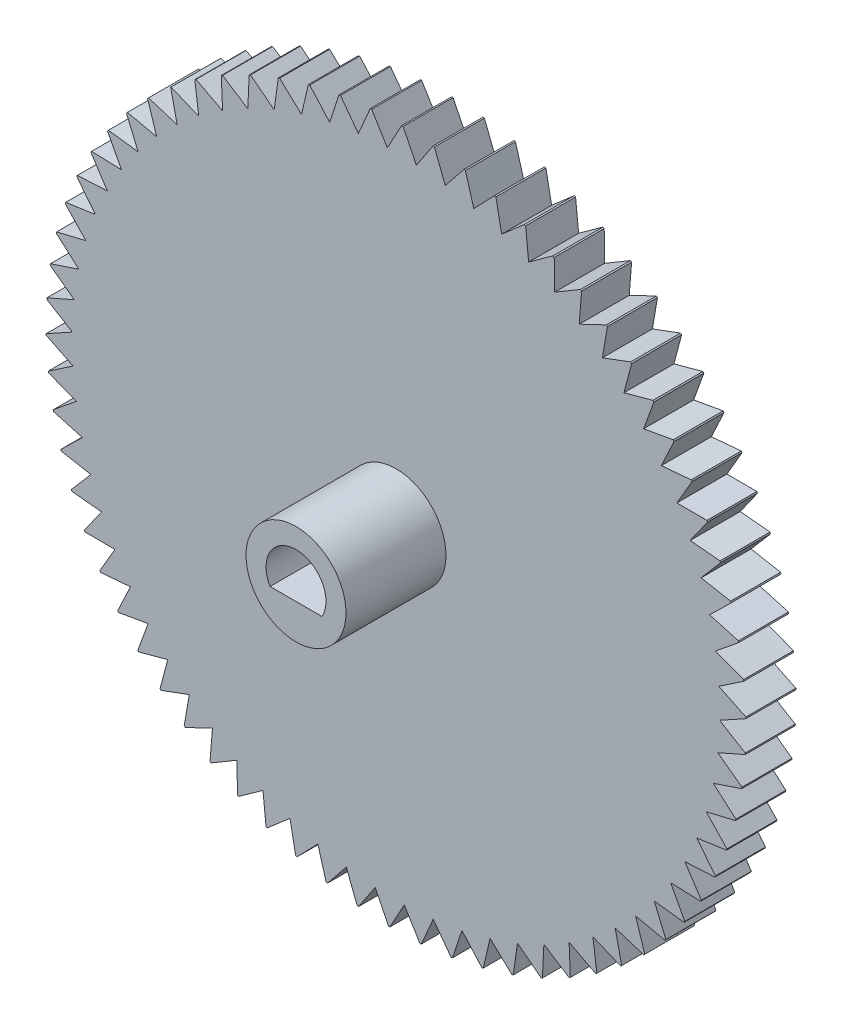
SolidWorks part; units mm, degrees
ref_plane "Front Plane" through (0, 0, 0) normal (0, 0, 1) x (1, 0, 0)
ref_plane "Top Plane" through (0, 0, 0) normal (0, 1, 0) x (1, 0, 0)
ref_plane "Right Plane" through (0, 0, 0) normal (1, 0, 0) x (0, 0, -1)
sketch "Sketch1" plane through (0, 0, 0) normal (0, 0, 1) x (1, 0, 0)
  circle A1 centre (0, 0) radius 35
  dimension "D2" = 70
extrude "Boss-Extrude1" add sketch "Sketch1" along normal blind 5
sketch "Sketch2" plane through (0, 0, 5) normal (0, 0, 1) x (1, 0, 0)
  line L0 (-24.7487, 24.7487) -> (-21.8869, 23.8488)
  line L1 (-21.8869, 23.8488) -> (-22.5385, 26.7772)
  circle A0 centre (0, 0) radius 35 construction
  dimension "D1" = 3
  dimension "D2" = 3
  dimension "D3" = 3
extrude "Cut-Extrude1" cut sketch "Sketch2" against normal blind 5 and the other way through all
pattern_circular "CirPattern1" count 70 every 5.145 about axis through (0, 0, 5) along (0, 0, 1) of "Cut-Extrude1"
sketch "Sketch3" plane through (0, 0, 5) normal (0, 0, 1) x (1, 0, 0)
  circle A0 centre (0, 0) radius 5
  dimension "D1" = 10
extrude "Boss-Extrude2" add sketch "Sketch3" along normal blind 10
sketch "Sketch4" plane through (0, 0, 0) normal (0, 0, -1) x (-1, 0, 0)
  circle A0 centre (0, 0) radius 3
  dimension "D1" = 6
extrude "Cut-Extrude2" cut sketch "Sketch4" against normal blind 6
sketch "Sketch5" plane through (0, 0, 6) normal (0, 0, -1) x (-1, 0, 0)
  line L1 (-2.5981, -1.5) -> (2.5981, -1.5)
  arc A1 (2.5981, -1.5) -> (-2.5981, -1.5) centre (0, 0) ccw
  dimension "D2" = 3
  dimension "D1" = 1.5
extrude "Cut-Extrude4" cut sketch "Sketch5" against normal blind 9
